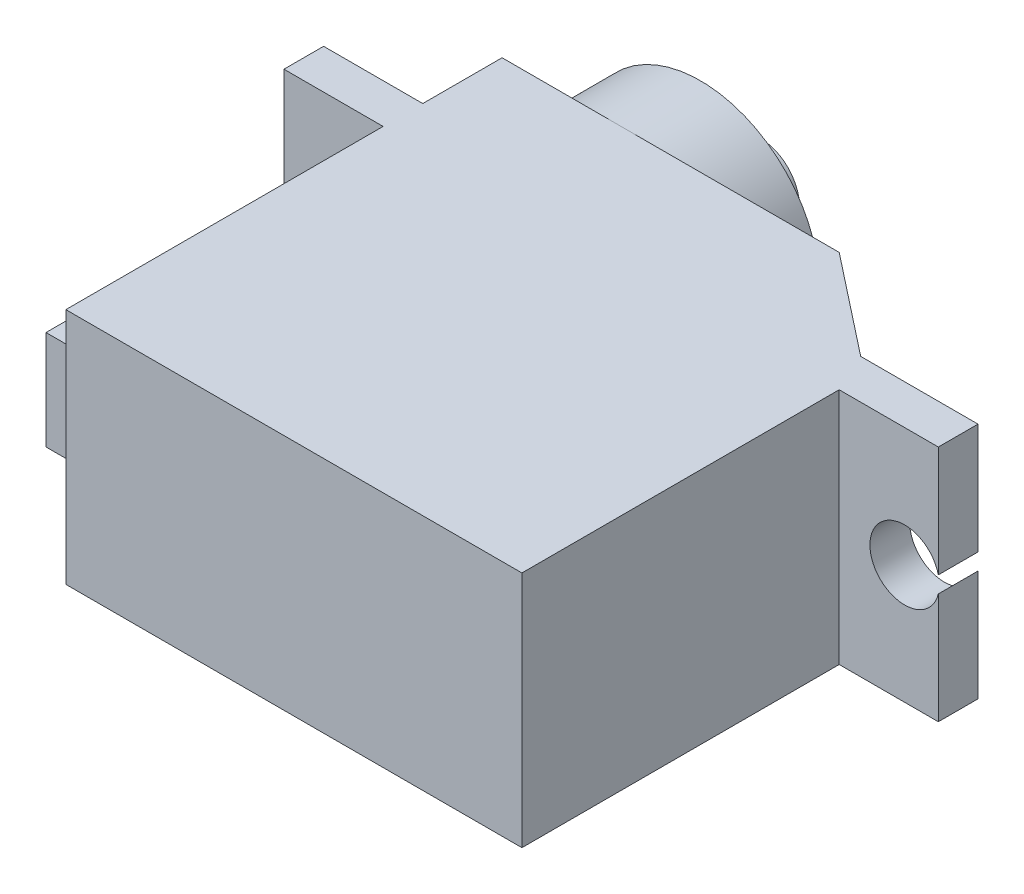
SolidWorks part; units mm, degrees
ref_plane "Plan de face" through (0, 0, 0) normal (0, 0, 1) x (1, 0, 0)
ref_plane "Plan de dessus" through (0, 0, 0) normal (0, 1, 0) x (1, 0, 0)
ref_plane "Plan de droite" through (0, 0, 0) normal (1, 0, 0) x (0, 0, -1)
sketch "Esquisse1" plane through (0, 0, 0) normal (0, 1, 0) x (1, 0, 0)
  line L0 (17, 22) -> (23, 17.2797)
  line L1 (0, 0) -> (23, 0)
  line L2 (0, 0) -> (0, 22)
  line L3 (0, 22) -> (17, 22)
  line L4 (23, 0) -> (23, 17.2797)
  dimension "D1" = 22
  dimension "D2" = 23
  dimension "D3" = 17
extrude "Boss.-Extru.1" add sketch "Esquisse1" along normal blind 12
sketch "Esquisse2" plane through (0, 0, 0) normal (-1, 0, 0) x (0, 0, 1)
  line L0 (-22, 0) -> (0, 0) construction
  line L1 (-18, 0) -> (-16, 0)
  line L2 (-18, 0) -> (-18, 12)
  line L3 (-18, 12) -> (-16, 12)
  line L4 (-16, 0) -> (-16, 12)
  line L5 (-22, 12) -> (0, 12) construction
  line L7 (0, 12) -> (0, 0) construction
  dimension "D1" = 2
  dimension "D2" = 16
extrude "Boss.-Extru.2" add sketch "Esquisse2" along normal blind 5 and the other way blind 28
sketch "Esquisse3" plane through (0, 0, -18) normal (0, 0, -1) x (-1, 0, 0)
  line L3 (0, 12) -> (5, 12) construction
  line L5 (0, 0) -> (0, 12) construction
  circle A0 centre (3.3, 6) radius 1.75
  dimension "D1" = 3.3
  dimension "D3" = 6
extrude "Enlèv. mat.-Extru.2" cut sketch "Esquisse3" against normal blind 5
sketch "Esquisse4" plane through (0, 0, -18) normal (0, 0, -1) x (-1, 0, 0)
  line L0 (-28, 0) -> (-22.0844, 0) construction
  line L2 (-28, 12) -> (-28, 0) construction
  circle A0 centre (-26.3, 6) radius 1.75
  dimension "D1" = 3.5
  dimension "D2" = 6
  dimension "D3" = 1.7
extrude "Enlèv. mat.-Extru.3" cut sketch "Esquisse4" against normal blind 5
sketch "Esquisse5" plane through (0, 0, -22) normal (0, 0, -1) x (-1, 0, 0)
  line L0 (0, 12) -> (0, 0) construction
  line L1 (-17, 0) -> (0, 0) construction
  circle A0 centre (-6, 6) radius 6
  dimension "D1" = 12
  dimension "D2" = 6
  dimension "D3" = 6
extrude "Boss.-Extru.3" add sketch "Esquisse5" along normal blind 4
sketch "Esquisse6" plane through (0, 0, -26) normal (0, 0, -1) x (-1, 0, 0)
  circle A0 centre (-6, 6) radius 2
  circle A1 centre (-6, 6) radius 6 construction
  dimension "D1" = 4
extrude "Boss.-Extru.4" add sketch "Esquisse6" along normal blind 3
sketch "Esquisse7" plane through (0, 0, 0) normal (-1, 0, 0) x (0, 0, 1)
  line L0 (-16, 12) -> (0, 12) construction
  line L1 (-2, 3.5) -> (-4, 3.5)
  line L2 (-2, 3.5) -> (-2, 8.5)
  line L3 (-2, 8.5) -> (-4, 8.5)
  line L4 (-4, 3.5) -> (-4, 8.5)
  line L5 (0, 12) -> (0, 0) construction
  dimension "D1" = 2
  dimension "D2" = 5
  dimension "D3" = 3.5
  dimension "D4" = 2
extrude "Boss.-Extru.5" add sketch "Esquisse7" along normal blind 3
